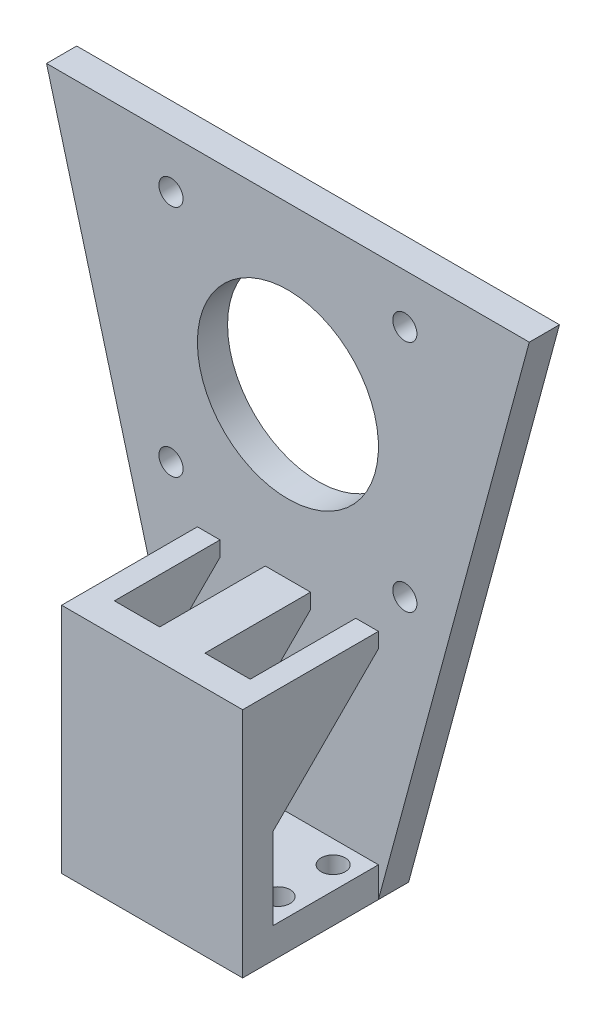
SolidWorks part; units mm, degrees
ref_plane "前视基准面" through (0, 0, 0) normal (0, 0, 1) x (1, 0, 0)
ref_plane "上视基准面" through (0, 0, 0) normal (0, 1, 0) x (1, 0, 0)
ref_plane "右视基准面" through (0, 0, 0) normal (1, 0, 0) x (0, 0, -1)
other "Configuration Table"
sketch "草图1" plane through (0, 0, 0) normal (0, 1, 0) x (1, 0, 0)
  line L1 (0, 0) -> (24, 0)
  line L2 (0, 0) -> (0, -14)
  line L3 (0, -14) -> (24, -14)
  line L4 (24, 0) -> (24, -14)
  circle A0 centre (3, -3) radius 1.6
  circle A1 centre (3, -11) radius 1.6
  circle A2 centre (21, -3) radius 1.6
  circle A3 centre (21, -10.3086) radius 1.6
  dimension "D3" = 3.2
  dimension "D4" = 3.2
  dimension "D6" = 3.2
  dimension "D7" = 3.2
  dimension "D1" = 14
  dimension "D2" = 24
  dimension "D5" = 8
  dimension "D8" = 18
  dimension "D9" = 18
  dimension "D10" = 3
  dimension "D11" = 3
  dimension "D12" = 3
  dimension "D13" = 3
extrude "凸台-拉伸1" add sketch "草图1" along normal blind 4
sketch "草图3" plane through (0, 0, 0) normal (0, 0, -1) x (-1, 0, 0)
  line L4 (-24, 0) -> (0, 0)
  line L5 (0, 0) -> (0, 4)
  line L6 (0, 4) -> (-24, 4)
  line L7 (-24, 4) -> (-24, 0)
  line L8 (-24, 0) -> (0, 0)
  line L9 (0, 0) -> (0, 4)
  line L10 (0, 4) -> (-24, 4)
  line L11 (-24, 4) -> (-24, 0)
  dimension "D1" = 0
extrude "凸台-拉伸2" add sketch "草图3" along normal blind 4
ref_plane "基准面1" through (0, 4, 0) normal (0, 1, 0) x (1, 0, 0)
sketch "草图4" plane through (0, 4, 0) normal (0, 1, 0) x (1, 0, 0)
  line L0 (0, 0) -> (24, 0)
  line L1 (24, -14) -> (24, 4) construction
sketch "草图5" plane through (0, 4, 0) normal (0, 1, 0) x (1, 0, 0)
  line L0 (0, 0) -> (0, 4)
  line L1 (0, 4) -> (24, 4)
  line L2 (24, 4) -> (24, 0)
  line L3 (0, 0) -> (24, 0)
extrude "凸台-拉伸3" add sketch "草图5" along normal blind 70
sketch "草图8" plane through (0, 0, 14) normal (0, 0, 1) x (1, 0, 0)
  line L4 (0, 0) -> (24, 0)
  line L5 (24, 0) -> (24, 4)
  line L6 (24, 4) -> (0, 4)
  line L7 (0, 4) -> (0, 0)
  line L8 (0, 0) -> (24, 0)
  line L9 (24, 0) -> (24, 4)
  line L10 (24, 4) -> (0, 4)
  line L11 (0, 4) -> (0, 0)
  dimension "D1" = 0
extrude "凸台-拉伸4" add sketch "草图8" along normal blind 4
sketch "草图9" plane through (0, 4, 0) normal (0, 1, 0) x (1, 0, 0)
  line L0 (0, -18) -> (0, -14)
  line L1 (0, 0) -> (0, -18) construction
  line L2 (0, -14) -> (24, -14)
  line L3 (24, -18) -> (24, 0) construction
  line L4 (24, -14) -> (24, -18)
  line L5 (24, -18) -> (0, -18)
extrude "凸台-拉伸5" add sketch "草图9" along normal blind 70
ref_plane "基准面2" through (0, 0, 18) normal (0, 0, 1) x (1, 0, 0)
ref_plane "基准面3" through (0, 0, -4) normal (0, 0, -1) x (-1, 0, 0)
sketch "草图10" plane through (0, 0, -4) normal (0, 0, -1) x (-1, 0, 0)
  line L0 (-24, 74) -> (0, 74)
  line L1 (0, 74) -> (20, 74)
  line L2 (-24, 74) -> (-44, 74)
  line L4 (-44, 74) -> (-24, 0)
  line L5 (-24, 0) -> (0, 0) construction
  line L6 (-24, 74) -> (-24, 0) construction
  line L7 (-24, 0) -> (0, 0)
  line L8 (0, 0) -> (20, 74)
extrude "凸台-拉伸7" add sketch "草图10" against normal blind 4
sketch "草图11" plane through (0, 0, -4) normal (0, 0, -1) x (-1, 0, 0)
  line L0 (-12, 52) -> (-27.5, 67.5) construction
  line L1 (-44, 74) -> (20, 74) construction
  circle A0 centre (-12, 52) radius 12
  circle A1 centre (-27.5, 67.5) radius 1.6
  circle A2 centre (3.5, 67.5) radius 1.6
  circle A3 centre (3.5, 36.5) radius 1.6
  circle A4 centre (-27.5, 36.5) radius 1.6
  dimension "D1" = 24
  dimension "D2" = 3.2
  dimension "D3" = 15.5
  dimension "D4" = 15.5
  dimension "D6" = 21.9203
  dimension "D7" = 22
  dimension "D5" = 4
sketch "草图13" plane through (0, 0, 18) normal (0, 0, 1) x (1, 0, 0)
  line L0 (-1.1007, 30.8) -> (25.2462, 30.8)
  line L1 (0, 74) -> (24, 74) construction
  dimension "D1" = 43.2
ref_plane "基准面4" through (0, 74, 0) normal (0, 1, 0) x (1, 0, 0)
sketch "草图14" plane through (0, 74, 0) normal (0, 1, 0) x (1, 0, 0)
  line L4 (0, -18) -> (24, -18)
  line L5 (24, -18) -> (24, -14)
  line L6 (24, -14) -> (0, -14)
  line L7 (0, -14) -> (0, -18)
  line L8 (0, -18) -> (24, -18)
  line L9 (24, -18) -> (24, -14)
  line L10 (24, -14) -> (0, -14)
  line L11 (0, -14) -> (0, -18)
  dimension "D1" = 0
extrude "切除-拉伸2" cut sketch "草图14" against normal blind 43.2
ref_plane "基准面5" through (0, 0, 0) normal (-1, 0, 0) x (0, 0, 1)
sketch "草图16" plane through (0, 0, 0) normal (-1, 0, 0) x (0, 0, 1)
  line L0 (14, 30.8) -> (0, 30.8)
  line L1 (14, 30.8) -> (14, 14.8)
  line L2 (14, 30.8) -> (14, 4) construction
  line L3 (0, 30.8) -> (0, 28.8)
  line L4 (0, 28.8) -> (14, 14.8)
ref_plane "基准面6" through (24, 0, 0) normal (1, 0, 0) x (0, 0, -1)
sketch "草图17" plane through (24, 0, 0) normal (1, 0, 0) x (0, 0, -1)
  line L0 (-14, 30.8) -> (-14, 14.8) construction
  line L1 (0, 30.8) -> (0, 28.8) construction
  line L2 (0, 28.8) -> (-14, 14.8) construction
  line L3 (-14, 30.8) -> (0, 30.8) construction
  line L4 (-14, 30.8) -> (-14, 14.8)
  line L5 (0, 30.8) -> (0, 28.8)
  line L6 (0, 28.8) -> (-14, 14.8)
  line L7 (-14, 30.8) -> (0, 30.8)
extrude "凸台-拉伸8" add sketch "草图17" against normal up to surface (24 mm away) up to plane "基准面5"
ref_plane "基准面7" through (0, 30.8, 0) normal (0, 1, 0) x (1, 0, 0)
sketch "草图18" plane through (0, 30.8, 0) normal (0, 1, 0) x (1, 0, 0)
  line L1 (24, -18) -> (12.0727, -18)
  line L2 (-1.1007, -18) -> (25.2462, -18) construction
  line L4 (15.0546, -18) -> (15.0546, 0)
  line L5 (0, 0) -> (24, 0) construction
  line L6 (21.0971, -18) -> (21.0971, 0)
  line L7 (0, -18) -> (12.0727, -18)
  line L8 (21.0971, 0) -> (21.0971, -18)
  line L9 (9.1032, -18) -> (3.0182, -18)
  line L10 (0, -14.0755) -> (24, -14.0755)
  line L11 (0, 0) -> (0, -18) construction
  line L12 (24, -18) -> (24, 0) construction
  line L13 (9.1032, -18) -> (9.1032, 0)
  line L14 (21.0971, 0) -> (21.0971, -14.0755)
  line L15 (3.0182, -18) -> (3.0182, 0)
  line L16 (3.0182, 0) -> (9.1032, 0)
  line L17 (12.1651, -18) -> (12.1651, 0)
  line L20 (21.0971, 0) -> (15.0546, 0)
  line L21 (21.0971, -14.0755) -> (15.0546, -14.0755)
  line L22 (15.0546, -14.0755) -> (15.0546, 0)
  line L23 (21.0971, 0) -> (15.0546, 0)
  line L24 (9.1032, 0) -> (3.0182, 0)
  line L25 (3.0182, 0) -> (3.0182, -14.0755)
  line L26 (3.0182, -14.0755) -> (9.1032, -14.0755)
  line L27 (9.1032, -14.0755) -> (9.1032, 0)
  line L28 (15.0546, -14.0755) -> (21.0971, -14.0755)
  line L29 (21.0971, 0) -> (21.0971, -14.0755)
  line L30 (21.0971, 0) -> (15.0546, 0)
  line L31 (15.0546, -14.0755) -> (15.0546, 0)
ref_plane "基准面8" through (12, 0, 0) normal (-1, 0, 0) x (0, 0, 1)
ref_plane "基准面9" through (6, 0, 0) normal (-1, 0, 0) x (0, 0, 1)
ref_plane "基准面10" through (18, 0, 0) normal (-1, 0, 0) x (0, 0, 1)
sketch "草图20" plane through (6, 0, 0) normal (-1, 0, 0) x (0, 0, 1)
  line L0 (14, 30.8) -> (14, 14.8) construction
  line L1 (0, 28.8) -> (14, 14.8) construction
  line L2 (0, 30.8) -> (0, 28.8) construction
  line L3 (14, 30.8) -> (0, 30.8) construction
  line L4 (14, 30.8) -> (14, 14.8)
  line L5 (0, 28.8) -> (14, 14.8)
  line L6 (0, 30.8) -> (0, 28.8)
  line L7 (14, 30.8) -> (0, 30.8)
extrude "切除-拉伸3" cut sketch "草图20" against normal blind 3 and the other way blind 3
sketch "草图21" plane through (18, 0, 0) normal (-1, 0, 0) x (0, 0, 1)
  line L0 (14, 30.8) -> (14, 14.8) construction
  line L1 (0, 28.8) -> (14, 14.8) construction
  line L2 (0, 30.8) -> (0, 28.8) construction
  line L3 (14, 30.8) -> (0, 30.8) construction
  line L4 (14, 30.8) -> (14, 14.8)
  line L5 (0, 28.8) -> (14, 14.8)
  line L6 (0, 30.8) -> (0, 28.8)
  line L7 (14, 30.8) -> (0, 30.8)
extrude "切除-拉伸4" cut sketch "草图21" against normal blind 3 and the other way blind 3
extrude "切除-拉伸6" cut sketch "草图11" against normal up to next contours A4 | A3 | A2 | A0 | A1
